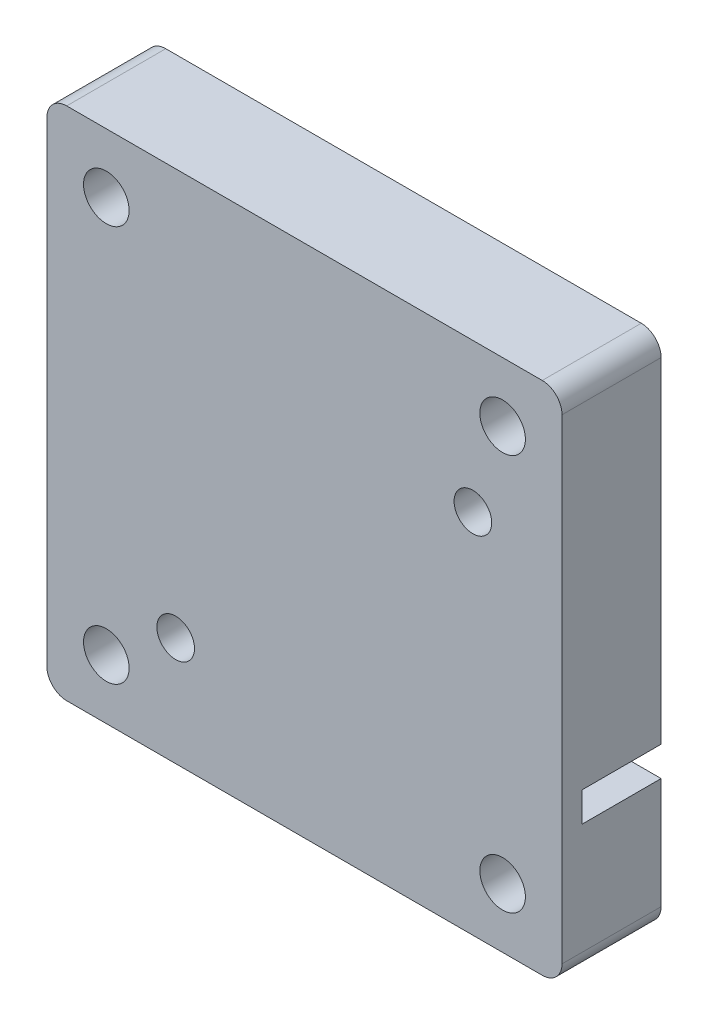
SolidWorks part; units mm, degrees
ref_plane "Front Plane" through (0, 0, 0) normal (0, 0, 1) x (1, 0, 0)
ref_plane "Top Plane" through (0, 0, 0) normal (0, 1, 0) x (1, 0, 0)
ref_plane "Right Plane" through (0, 0, 0) normal (1, 0, 0) x (0, 0, -1)
sketch "Sketch1" plane through (0, 0, 0) normal (0, 0, 1) x (1, 0, 0)
  line L0 (-1, 9) -> (-1, 1) construction
  line L1 (-11, 11) -> (-11, -9) construction
  line L2 (-14, -12) -> (12, -12)
  line L3 (-14, -12) -> (-14, 14)
  line L4 (-14, 14) -> (12, 14)
  line L5 (12, -12) -> (12, 14)
  line L6 (-14, -12) -> (12, 14) construction
  line L7 (-14, 14) -> (12, -12) construction
  line L8 (-11, -9) -> (9, -9) construction
  line L9 (9, -9) -> (9, 11) construction
  line L10 (9, 11) -> (-11, 11) construction
  line L12 (-5.5, -1.6) -> (6.6, -1.6)
  line L13 (-5.5, -1.6) -> (-5.5, -7.7)
  line L14 (-5.5, -7.7) -> (6.6, -7.7)
  line L15 (6.6, -1.6) -> (6.6, -7.7)
  circle A0 centre (-11, 11) radius 1.15
  circle A1 centre (9, 11) radius 1.15
  circle A2 centre (9, -9) radius 1.15
  circle A3 centre (-11, -9) radius 1.15
  circle A4 centre (7.5, 6.5) radius 0.95
  circle A5 centre (-7.5, -6.5) radius 0.95
  point P4 (-1, 1)
  dimension "D3" = 20
  dimension "D5" = 1.9
  dimension "D2" = 2.3
  dimension "D1" = 26
  dimension "D4" = 8
extrude "Boss-Extrude1" add sketch "Sketch1" along normal blind 4
sketch "Sketch7" plane through (0, 0, 4) normal (0, 0, 1) x (1, 0, 0)
  line L4 (12, -12) -> (12, 14)
  line L5 (12, 14) -> (-14, 14)
  line L6 (-14, 14) -> (-14, -12)
  line L7 (-14, -12) -> (12, -12)
  line L8 (12, -12) -> (12, 14)
  line L9 (12, 14) -> (-14, 14)
  line L10 (-14, 14) -> (-14, -12)
  line L11 (-14, -12) -> (12, -12)
  circle A0 centre (7.5, 6.5) radius 0.95 construction
  circle A1 centre (-7.5, -6.5) radius 0.95 construction
  circle A2 centre (-11, -9) radius 1.15 construction
  circle A3 centre (9, -9) radius 1.15 construction
  circle A4 centre (9, 11) radius 1.15 construction
  circle A5 centre (-11, 11) radius 1.15 construction
  circle A6 centre (7.5, 6.5) radius 0.95
  circle A7 centre (-7.5, -6.5) radius 0.95
  circle A8 centre (-11, -9) radius 1.15
  circle A9 centre (9, -9) radius 1.15
  circle A10 centre (9, 11) radius 1.15
  circle A11 centre (-11, 11) radius 1.15
  dimension "D1" = 0
extrude "Boss-Extrude4" add sketch "Sketch7" along normal blind 1
sketch "Sketch8" plane through (0, 0, 0) normal (0, 0, -1) x (-1, 0, 0)
  circle A0 centre (-9, 11) radius 2.1
  circle A1 centre (11, 11) radius 2.1
  circle A2 centre (11, -9) radius 2.1
  circle A3 centre (-9, -9) radius 2.1
  dimension "D1" = 4.2
extrude "Cut-Extrude5" cut sketch "Sketch8" against normal blind 2.2
sketch "Sketch3" plane through (0, 0, 0) normal (0, 0, -1) x (-1, 0, 0)
  line L0 (-6.6, -4.65) -> (-12, -4.65) construction
  line L1 (-6.6, -7.7) -> (-6.6, -1.6) construction
  line L2 (-12, -12) -> (-12, 14) construction
  line L4 (-12, -5.4) -> (-6.6, -5.4)
  line L5 (-12, -5.4) -> (-12, -3.9)
  line L6 (-12, -3.9) -> (-6.6, -3.9)
  line L7 (-6.6, -5.4) -> (-6.6, -3.9)
  line L8 (-12, -5.4) -> (-6.6, -3.9) construction
  line L9 (-12, -3.9) -> (-6.6, -5.4) construction
  point P6 (-9.3, -4.65)
  dimension "D1" = 1.5
extrude "Cut-Extrude6" cut sketch "Sketch3" against normal up to surface (4 mm away) up to face at (0.55, -4.65, 4)
chamfer "Chamfer2" distance 1.5 angle 45 2 edges at (6.6, -3.9, 2) (6.6, -5.4, 2)
fillet "Fillet1" radius 1 4 edges at (-14, -12, 2.5) (12, -12, 2.5) (12, 14, 2.5) (-14, 14, 2.5)
